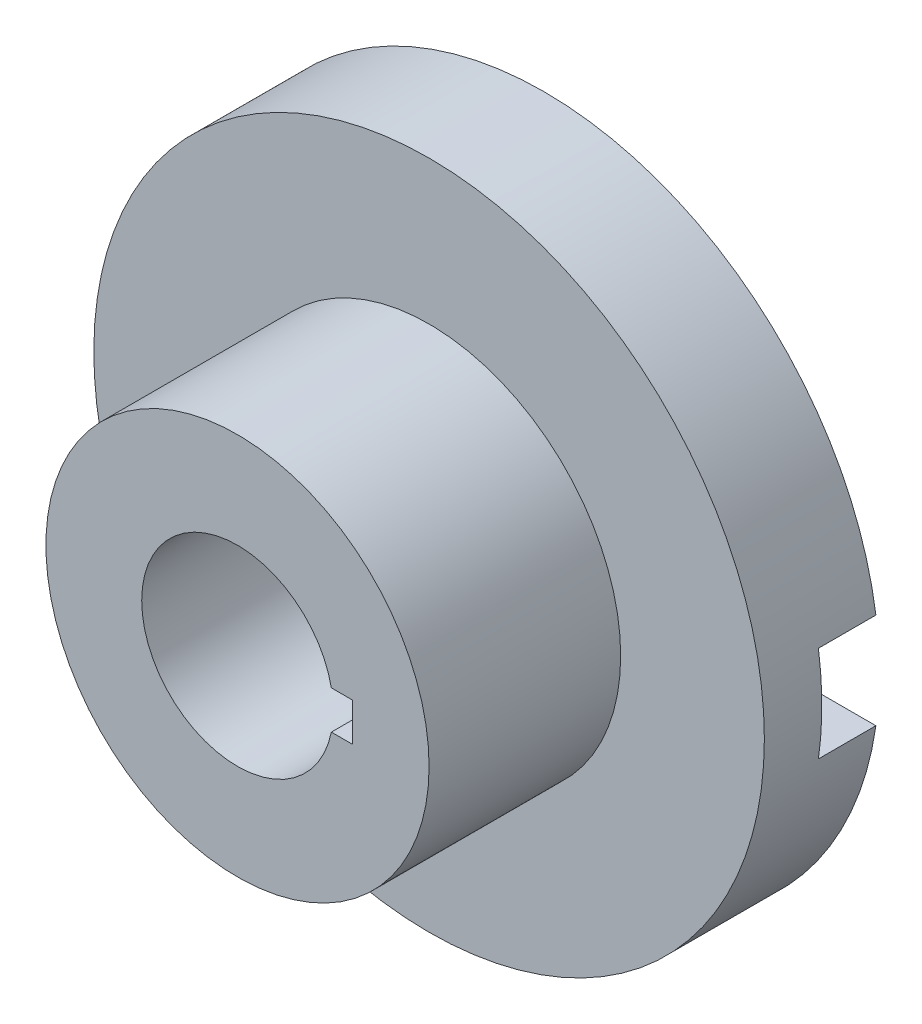
SolidWorks part; units mm, degrees
material "AISI 1045 Steel, cold drawn"
ref_plane "Front Plane" through (0, 0, 0) normal (0, 0, 1) x (1, 0, 0)
ref_plane "Top Plane" through (0, 0, 0) normal (0, 1, 0) x (1, 0, 0)
ref_plane "Right Plane" through (0, 0, 0) normal (1, 0, 0) x (0, 0, -1)
sketch "Sketch1" plane through (0, 0, 0) normal (0, 0, 1) x (1, 0, 0)
  circle A0 centre (0, 0) radius 175
  dimension "D1" = 350
extrude "Boss-Extrude1" add sketch "Sketch1" along normal blind 60
sketch "Sketch2" plane through (0, 0, 60) normal (0, 0, 1) x (1, 0, 0)
  circle A0 centre (0, 0) radius 100
  dimension "D1" = 200
extrude "Boss-Extrude2" add sketch "Sketch2" along normal blind 100
sketch "Sketch4" plane through (0, 0, 0) normal (0, 0, 1) x (1, 0, 0)
  line L0 (220.9125, 0) -> (-220.9125, 0) construction
  line L1 (173.2051, 25) -> (-173.2051, 25)
  line L2 (173.2051, -25) -> (-173.2051, -25)
  arc A0 (-173.2051, 25) -> (-173.2051, -25) centre (0, 0) ccw
  arc A1 (173.2051, -25) -> (173.2051, 25) centre (0, 0) ccw
  point P5 (0, 0)
  dimension "D4" = 350
  dimension "D1" = 25
  dimension "D2" = 25
  dimension "D3" = 50
extrude "Cut-Extrude1" cut sketch "Sketch4" along normal blind 30 contours L1 A0 L2 A1
sketch "Sketch6" plane through (0, 0, 160) normal (0, 0, 1) x (1, 0, 0)
  line L0 (-138.1002, 0) -> (138.1002, 0) construction
  line L1 (59.9998, 10) -> (59.9998, -10)
  line L2 (59.9998, 10) -> (48.9898, 10)
  line L3 (59.9998, -10) -> (48.9898, -10)
  arc A0 (48.9898, 10) -> (48.9898, -10) centre (0, 0) ccw
  point P6 (0, 0)
  point P8 (59.9998, 0)
  dimension "D1" = 100
  dimension "D2" = 0
  dimension "D3" = 20
  dimension "D4" = 11.01
  dimension "D5" = 11.01
extrude "Cut-Extrude2" cut sketch "Sketch6" against normal through all
